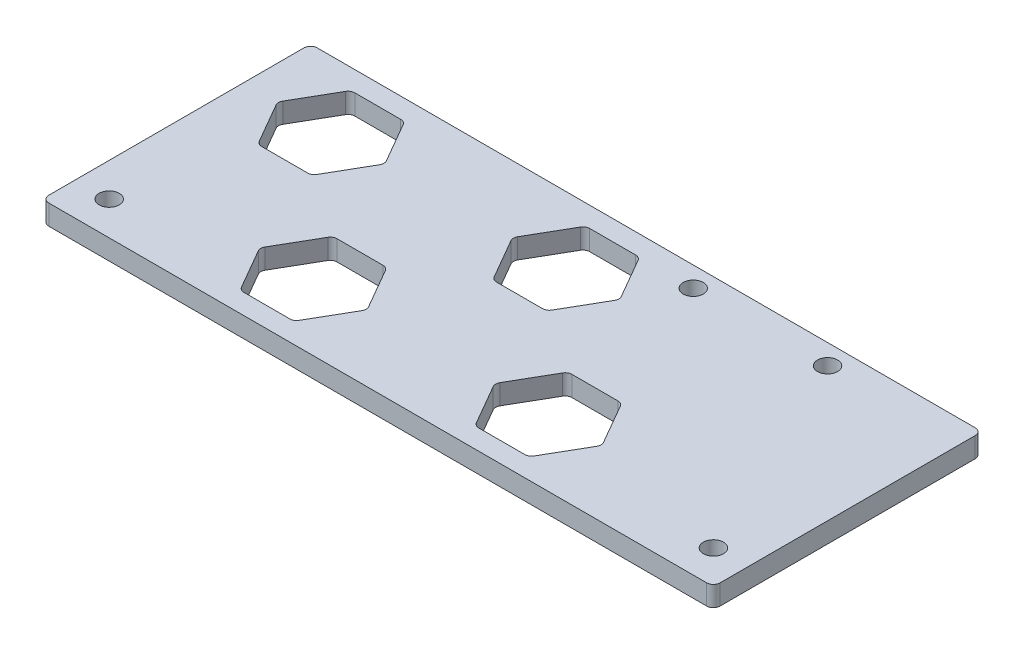
SolidWorks part; units mm, degrees
ref_plane "前视基准面" through (0, 0, 0) normal (0, 0, 1) x (1, 0, 0)
ref_plane "上视基准面" through (0, 0, 0) normal (0, 1, 0) x (1, 0, 0)
ref_plane "右视基准面" through (0, 0, 0) normal (1, 0, 0) x (0, 0, -1)
other "Configuration Table"
sketch "草图1" plane through (0, 0, 0) normal (0, 1, 0) x (1, 0, 0)
  line L1 (-50, 20) -> (50, 20)
  line L2 (-50, 20) -> (-50, -20)
  line L3 (-50, -20) -> (50, -20)
  line L4 (50, 20) -> (50, -20)
  line L5 (-50, 20) -> (50, -20) construction
  line L6 (-50, -20) -> (50, 20) construction
  point P0 (0, 0)
  dimension "D1" = 100
  dimension "D2" = 40
extrude "凸台-拉伸1" add sketch "草图1" along normal blind 3
sketch "草图2" plane through (0, 3, 0) normal (0, 1, 0) x (1, 0, 0)
  line L0 (10, 17) -> (30, 17) construction
  line L1 (50, 20) -> (-50, 20) construction
  line L2 (50, -20) -> (50, 20) construction
  circle A0 centre (10, 17) radius 1.5
  circle A1 centre (30, 17) radius 1.5
  dimension "D2" = 3
  dimension "D1" = 20
  dimension "D3" = 3
  dimension "D4" = 20
extrude "切除-拉伸1" cut sketch "草图2" against normal blind 3
fillet "圆角1" radius 1 4 edges at (50, 1.5, 20) (-50, 1.5, 20) (50, 1.5, -20) (-50, 1.5, -20)
sketch "草图3" plane through (0, 3, 0) normal (0, 1, 0) x (1, 0, 0)
  line L1 (-29, 10.0718) -> (-33, 17)
  line L2 (-33, 17) -> (-41, 17)
  line L3 (-41, 17) -> (-45, 10.0718)
  line L4 (-45, 10.0718) -> (-41, 3.1436)
  line L5 (-41, 3.1436) -> (-33, 3.1436)
  line L6 (-33, 3.1436) -> (-29, 10.0718)
  line L7 (-11.5036, -10.0718) -> (-15.5036, -3.1436)
  line L8 (-15.5036, -3.1436) -> (-23.5036, -3.1436)
  line L9 (-23.5036, -3.1436) -> (-27.5036, -10.0718)
  line L10 (-27.5036, -10.0718) -> (-23.5036, -17)
  line L11 (-23.5036, -17) -> (-15.5036, -17)
  line L12 (-15.5036, -17) -> (-11.5036, -10.0718)
  line L13 (49, 20) -> (-49, 20) construction
  line L14 (-49, -20) -> (49, -20) construction
  line L15 (-50, 19) -> (-50, -19) construction
  line L16 (5.9927, 10.0718) -> (1.9927, 17)
  line L17 (1.9927, 17) -> (-6.0073, 17)
  line L18 (-6.0073, 17) -> (-10.0073, 10.0718)
  line L19 (-10.0073, 10.0718) -> (-6.0073, 3.1436)
  line L20 (-6.0073, 3.1436) -> (1.9927, 3.1436)
  line L21 (1.9927, 3.1436) -> (5.9927, 10.0718)
  line L22 (23.4891, -10.0718) -> (19.4891, -3.1436)
  line L23 (19.4891, -3.1436) -> (11.4891, -3.1436)
  line L24 (11.4891, -3.1436) -> (7.4891, -10.0718)
  line L25 (7.4891, -10.0718) -> (11.4891, -17)
  line L26 (11.4891, -17) -> (19.4891, -17)
  line L27 (19.4891, -17) -> (23.4891, -10.0718)
  line L28 (-19.5036, -10.0718) -> (-19.5036, 20) construction
  circle A0 centre (-37, 10.0718) radius 6.9282 construction
  circle A1 centre (-19.5036, -10.0718) radius 6.9282 construction
  dimension "D1" = 17.4964
  dimension "D2" = 8
  dimension "D3" = 3
  dimension "D4" = 3
  dimension "D5" = 13
  dimension "D6" = 2
extrude "切除-拉伸2" cut sketch "草图3" against normal blind 10
fillet "圆角2" radius 1 24 edges at (11.4891, 1.5, 17) (7.4891, 1.5, 10.0718) (11.4891, 1.5, 3.1436) (19.4891, 1.5, 3.1436) (23.4891, 1.5, 10.0718) (19.4891, 1.5, 17) (-23.5036, 1.5, 17) (-27.5036, 1.5, 10.0718) (-23.5036, 1.5, 3.1436) (-15.5036, 1.5, 3.1436) (-11.5036, 1.5, 10.0718) (-15.5036, 1.5, 17) (-6.0073, 1.5, -3.1436) (-10.0073, 1.5, -10.0718) (-6.0073, 1.5, -17) (1.9927, 1.5, -17) (5.9927, 1.5, -10.0718) (1.9927, 1.5, -3.1436) (-41, 1.5, -3.1436) (-41, 1.5, -17) (-33, 1.5, -17) (-29, 1.5, -10.0718) (-33, 1.5, -3.1436) (-45, 1.5, -10.0718)
sketch "草图4" plane through (0, 3, 0) normal (0, 1, 0) x (1, 0, 0)
  line L0 (-45, -15) -> (45, -15) construction
  line L1 (0, 0) -> (0, -15) construction
  line L2 (50, -19) -> (50, 19) construction
  line L3 (-49, -20) -> (49, -20) construction
  circle A0 centre (-45, -15) radius 1.5
  circle A1 centre (45, -15) radius 1.5
  dimension "D1" = 3
  dimension "D2" = 5
  dimension "D3" = 5
extrude "切除-拉伸3" cut sketch "草图4" against normal blind 10
